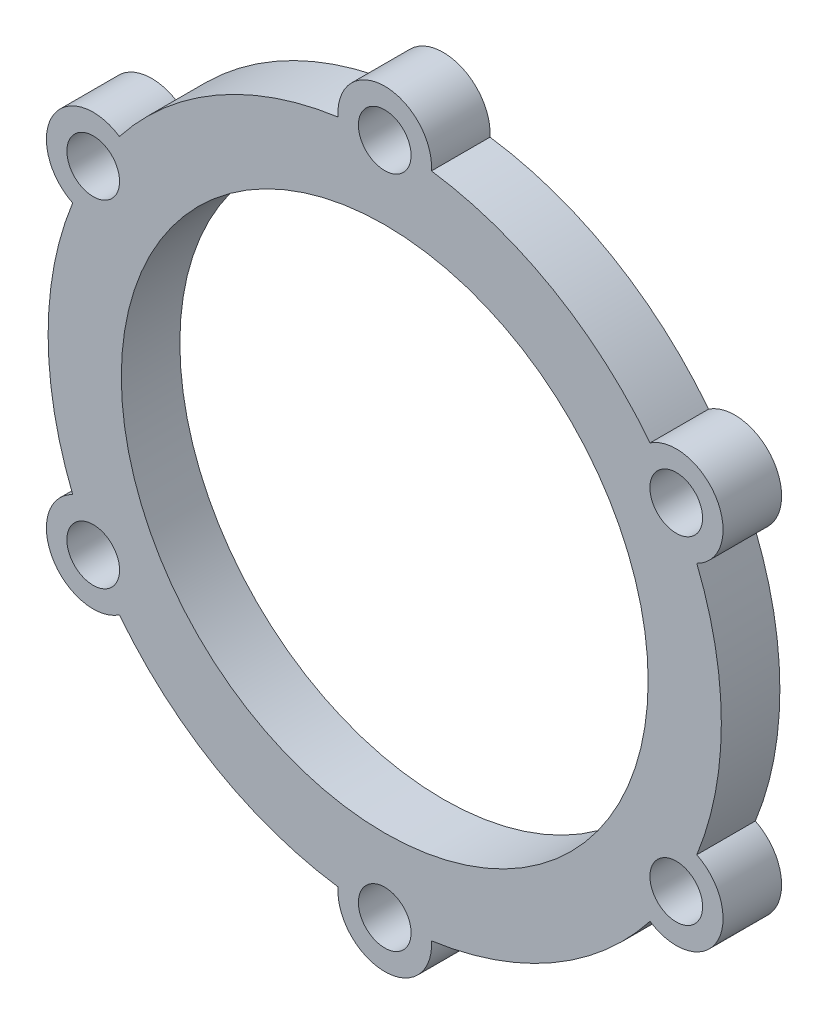
SolidWorks part; units mm, degrees
ref_plane "Front Plane" through (0, 0, 0) normal (1, 0, 0) x (0, 1, 0)
ref_plane "Top Plane" through (0, 0, 0) normal (0, 0, 1) x (0, 1, 0)
ref_plane "Right Plane" through (0, 0, 0) normal (0, 1, 0) x (-1, 0, 0)
sketch "Sketch2" plane through (0, 0, 0) normal (0, 0, 1) x (0, 1, 0)
  line L0 (0, 0) -> (86.8373, 0) construction
  line L1 (0, 0) -> (0, 62.9004) construction
  line L2 (0, 0) -> (37.6537, 65.2181) construction
  arc A0 (21.5603, 53.3048) -> (-21.5603, 53.3048) centre (0, 0) ccw
  circle A1 centre (0, 0) radius 45
  circle A2 centre (28.75, 49.7965) radius 4.5
  circle A3 centre (28.75, 49.7965) radius 8
  circle A4 centre (57.5, 0) radius 4.5
  circle A5 centre (57.5, 0) radius 8
  circle A6 centre (28.75, -49.7965) radius 4.5
  circle A7 centre (28.75, -49.7965) radius 8
  circle A8 centre (-28.75, -49.7965) radius 4.5
  circle A9 centre (-28.75, -49.7965) radius 8
  circle A10 centre (-57.5, 0) radius 4.5
  circle A11 centre (-57.5, 0) radius 8
  circle A12 centre (-28.75, 49.7965) radius 4.5
  circle A13 centre (-28.75, 49.7965) radius 8
  arc A14 (-35.3832, 45.3242) -> (-56.9435, 7.9806) centre (0, 0) ccw
  arc A15 (-56.9435, -7.9806) -> (-35.3832, -45.3242) centre (0, 0) ccw
  arc A16 (-21.5603, -53.3048) -> (21.5603, -53.3048) centre (0, 0) ccw
  arc A17 (35.3832, -45.3242) -> (56.9435, -7.9806) centre (0, 0) ccw
  arc A18 (56.9435, 7.9806) -> (35.3832, 45.3242) centre (0, 0) ccw
  point P29 (0, 0)
  dimension "D1" = 115
  dimension "D2" = 90
  dimension "D4" = 9
  dimension "D5" = 16
  dimension "D3" = 60
  dimension "D6" = 6
extrude "Boss-Extrude1" add sketch "Sketch2" along normal blind 10 contours A5 A18 A3 A0 A13 A14 A11 A15 A9 A16 A7 A17 A1 | A9 A8 | A7 A6 | A5 A4 | A3 A2 | A13 A12 | A10
